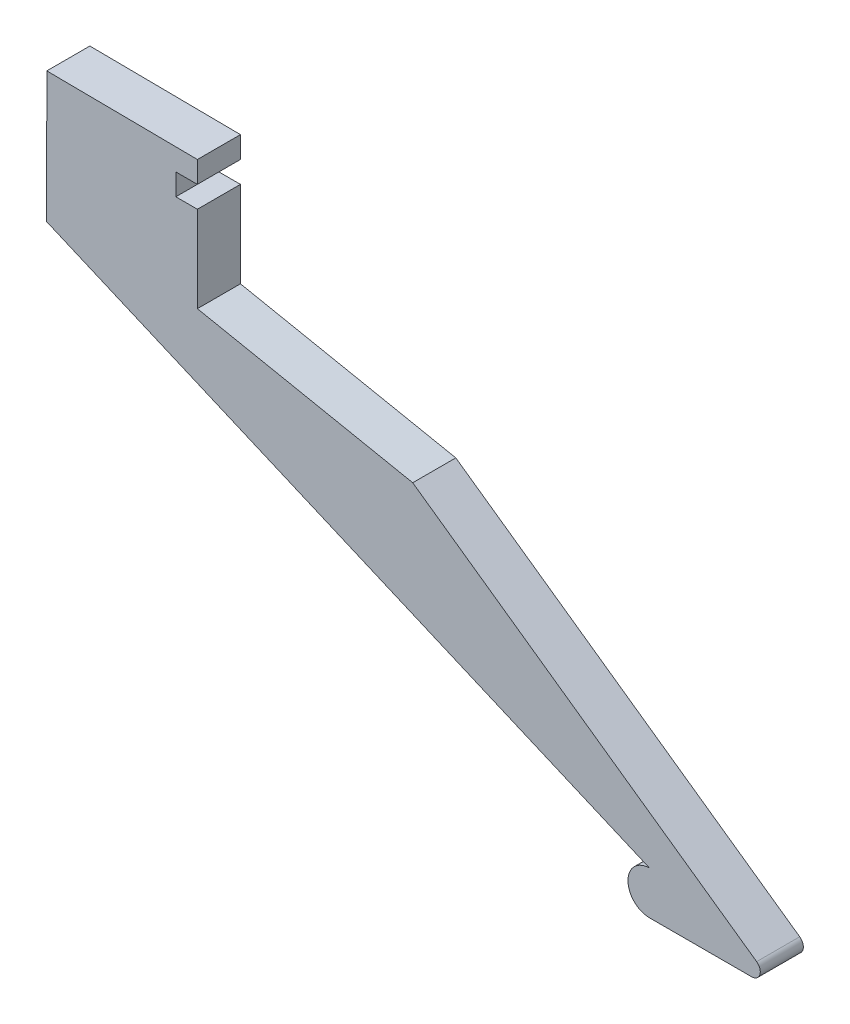
SolidWorks part; units mm, degrees
ref_plane "Front Plane" through (0, 0, 0) normal (0, 0, 1) x (1, 0, 0)
ref_plane "Top Plane" through (0, 0, 0) normal (0, 1, 0) x (1, 0, 0)
ref_plane "Right Plane" through (0, 0, 0) normal (1, 0, 0) x (0, 0, -1)
sketch "Sketch1" plane through (0, 0, 0) normal (0, 0, 1) x (1, 0, 0)
  line L0 (-24.4708, 23.2414) -> (-24.4829, 13.6087)
  line L1 (-24.4708, 23.2414) -> (-13.3704, 23.1337)
  line L3 (19.9543, -8.6163) -> (27.4921, -8.6163)
  line L5 (-24.4829, 13.6087) -> (19.9671, -5.4413)
  line L13 (-13.3704, 13.6087) -> (-13.3704, 23.1337)
  line L16 (-13.3704, 13.6087) -> (2.5046, 10.4337)
  line L17 (2.5046, 10.4337) -> (27.8582, -7.4629)
  arc A0 (19.9671, -5.4413) -> (19.9543, -8.6163) centre (19.9607, -7.0288) ccw
  arc A1 (27.8582, -7.4629) -> (27.4921, -8.6163) centre (27.4921, -7.9815) cw
extrude "Boss-Extrude1" add sketch "Sketch1" along normal blind 3.175
ref_plane "Plane1" through (0, 0, 3.175) normal (0, 0, 1) x (1, 0, 0)
sketch "Sketch2" plane through (0, 0, 3.175) normal (0, 0, 1) x (1, 0, 0)
  line L0 (-13.3704, 23.1337) -> (-13.3704, 21.5462)
  line L1 (-13.3704, 13.6087) -> (-13.3704, 23.1337) construction
  line L2 (-13.3704, 21.5462) -> (-13.3704, 19.9587)
  line L3 (-13.3704, 21.5462) -> (-14.9579, 21.5462)
  line L4 (-13.3704, 19.9587) -> (-14.9579, 19.9587)
  line L5 (-14.9579, 21.5462) -> (-14.9579, 19.9587)
  dimension "D1" = 1.5875
  dimension "D2" = 1.5875
  dimension "D3" = 1.5875
  dimension "D4" = 1.5875
extrude "Cut-Extrude1" cut sketch "Sketch2" against normal blind 3.175 contours L3 L5 L4 L2
